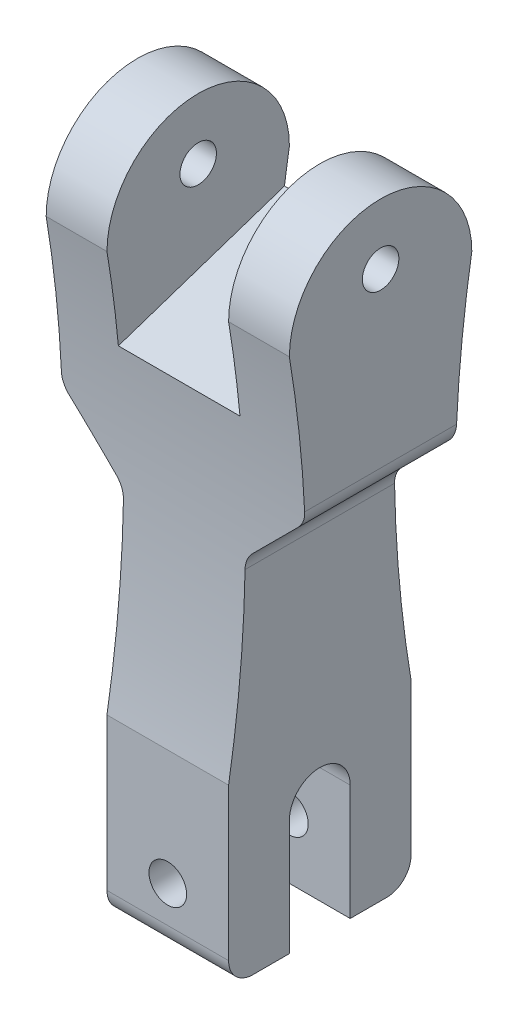
SolidWorks part; units mm, degrees
ref_plane "Front Plane" through (0, 0, 0) normal (0, 0, 1) x (1, 0, 0)
ref_plane "Top Plane" through (0, 0, 0) normal (0, 1, 0) x (1, 0, 0)
ref_plane "Right Plane" through (0, 0, 0) normal (1, 0, 0) x (0, 0, -1)
sketch "Croquis1" plane through (0, 0, 0) normal (0, 0, 1) x (1, 0, 0)
  line L0 (-5, 25) -> (-10, 30)
  line L1 (-10, 30) -> (-10, 50)
  line L2 (-5, 25) -> (-5, -5)
  line L3 (-5, -5) -> (5, -5)
  line L4 (5, 25) -> (5, -5)
  line L5 (-10, 50) -> (10, 50)
  line L10 (10, 50) -> (10, 30)
  line L11 (10, 30) -> (5, 25)
  circle A0 centre (0, 0) radius 1.55
  circle A1 centre (0, 40) radius 10 construction
  point P3 (0, -5)
  point P9 (0, 50)
  point P12 (-10, 40)
  dimension "D1" = 3.1
  dimension "D2" = 5
  dimension "D3" = 10
  dimension "D5" = 20
  dimension "D4" = 45
  dimension "D6" = 55
  dimension "D7" = 25
extrude "Saliente-Extruir1" add sketch "Croquis1" along normal blind 15
sketch "Croquis8" plane through (0, 0, 15) normal (0, 0, 1) x (1, 0, 0)
  line L0 (-10, 50) -> (10, 50) construction
  line L1 (5, 50) -> (-5, 50)
  line L2 (5, 50) -> (5, 35)
  line L3 (5, 35) -> (-5, 35)
  line L4 (-5, 50) -> (-5, 35)
  point P6 (0, 50)
  dimension "D1" = 10
  dimension "D2" = 15
sketch "Croquis9" plane through (0, 0, 0) normal (0, 0, -1) x (-1, 0, 0)
  line L0 (-5, 50) -> (-5, 35) construction
  line L1 (5, 50) -> (-5, 50)
  line L2 (5, 50) -> (5, 40)
  line L3 (5, 40) -> (-5, 40)
  line L4 (-5, 50) -> (-5, 40)
  dimension "D1" = 10
loft "Cortar-Recubrir1" cut profiles "Croquis8", "Croquis9"
fillet "Redondeo1" radius 2 6 edges at (0, -5, 15) (0, -5, 0) (-10, 30, 7.5) (-5, 25, 7.5) (5, 25, 7.5) (10, 30, 7.5)
sketch "Croquis10" plane through (10, 0, 0) normal (1, 0, 0) x (0, 0, -1)
  line L0 (-15, 50) -> (0, 50) construction
  line L1 (-7.5, -5) -> (-7.5, 4.5) construction
  line L2 (-10, -5) -> (-10, 4.5)
  line L3 (-5, -5) -> (-5, 4.5)
  line L4 (-13, -5) -> (-2, -5) construction
  line L6 (-15, 50) -> (-15, 30.8284) construction
  line L7 (-17.5, 9.5) -> (-15, 9.5)
  line L8 (-17.5, 9.5) -> (-17.5, 51.5)
  line L9 (-17.5, 51.5) -> (2.5, 51.5)
  line L10 (2.5, 51.5) -> (2.5, 9.5)
  line L11 (0, 9.5) -> (2.5, 9.5)
  line L12 (-15, 24.1716) -> (-15, -3) construction
  circle A0 centre (-7.5, 45) radius 1.5
  arc A1 (-10, -5) -> (-5, -5) centre (-7.5, -5) ccw
  arc A2 (-5, 4.5) -> (-10, 4.5) centre (-7.5, 4.5) ccw
  circle A3 centre (-7.5, 42.5) radius 7.5 construction
  arc A4 (0, 42.5) -> (-15, 42.5) centre (-7.5, 42.5) ccw
  circle A5 centre (-7.5, 9.5) radius 7.5 construction
  arc A6 (-15, 42.5) -> (-15, 9.5) centre (-113.6294, 26) cw
  arc A7 (0, 42.5) -> (0, 9.5) centre (98.6294, 26) ccw
  point P5 (-7.5, 50)
  point P7 (-7.5, -0.25)
  point P16 (-7.5, 7)
  point P27 (-7.5, 51.5)
  point P34 (-7.5, 50)
  dimension "D1" = 3
  dimension "D5" = 20
  dimension "D7" = 5
  dimension "D8" = 100
  dimension "D9" = 100
  dimension "D2" = 45
  dimension "D3" = 5
  dimension "D4" = 12
  dimension "D6" = 42
extrude "Cortar-Extruir1" cut sketch "Croquis10" against normal through all
